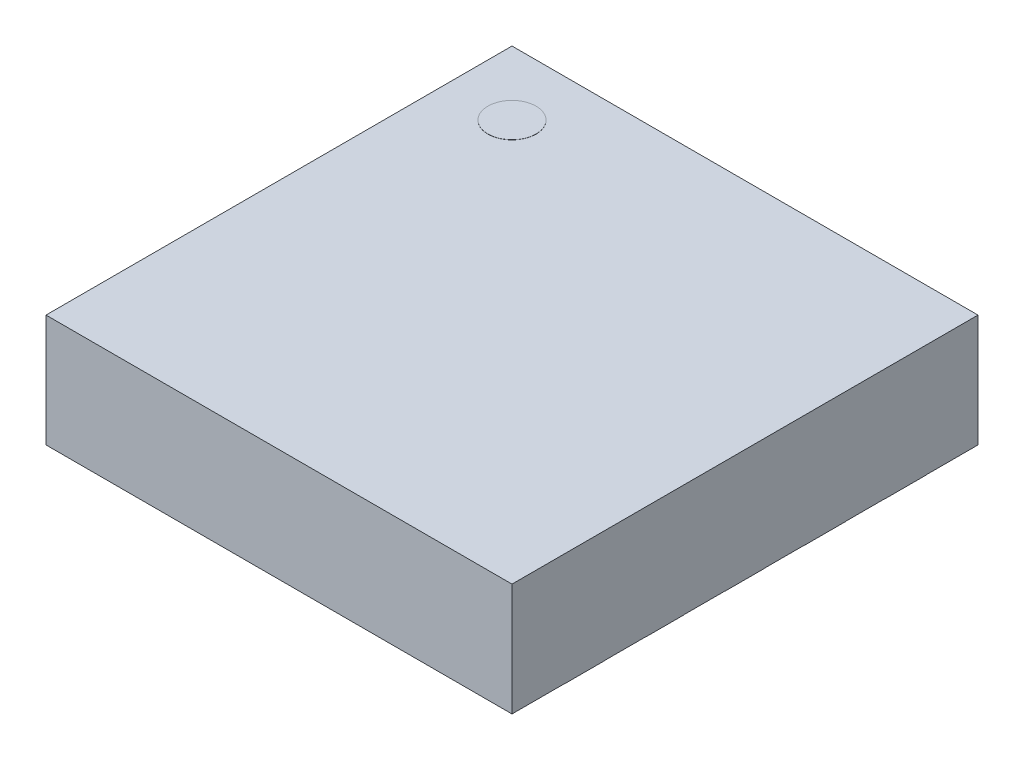
SolidWorks part; units mm, degrees
ref_plane "Front Plane" through (0, 0, 0) normal (0, 0, 1) x (1, 0, 0)
ref_plane "Top Plane" through (0, 0, 0) normal (0, 1, 0) x (1, 0, 0)
ref_plane "Right Plane" through (0, 0, 0) normal (1, 0, 0) x (0, 0, -1)
sketch "Sketch1" plane through (0, 0, 0) normal (0, 1, 0) x (1, 0, 0)
  line L1 (-1.45, 1.45) -> (1.45, 1.45)
  line L2 (-1.45, 1.45) -> (-1.45, -1.45)
  line L3 (-1.45, -1.45) -> (1.45, -1.45)
  line L4 (1.45, 1.45) -> (1.45, -1.45)
  line L5 (-1.45, 1.45) -> (1.45, -1.45) construction
  line L6 (-1.45, -1.45) -> (1.45, 1.45) construction
  point P0 (0, 0)
  dimension "D1" = 2.9
  dimension "D2" = 2.9
extrude "Boss-Extrude1" add sketch "Sketch1" along normal blind 0.7
sketch "Sketch2" plane through (0, 0, 0) normal (0, -1, 0) x (1, 0, 0)
  line L0 (0, 0) -> (-1.288, 0) construction
  line L1 (-1.45, -1.45) -> (-1.45, 1.45) construction
  line L2 (-1.45, 0.125) -> (-1.126, 0.125)
  line L3 (-1.45, 0.125) -> (-1.45, -0.125)
  line L4 (-1.45, -0.125) -> (-1.126, -0.125)
  line L5 (-1.126, 0.125) -> (-1.126, -0.125)
  line L6 (-1.45, 0.125) -> (-1.126, -0.125) construction
  line L7 (-1.45, -0.125) -> (-1.126, 0.125) construction
  line L8 (0, 0) -> (0, 0.6046) construction
  line L9 (-1.45, 0.625) -> (-1.45, 0.375)
  line L10 (-1.45, 0.625) -> (-1.126, 0.625)
  line L11 (-1.126, 0.625) -> (-1.126, 0.375)
  line L12 (-1.45, 0.375) -> (-1.126, 0.375)
  line L13 (-1.45, 1.125) -> (-1.45, 0.875)
  line L14 (-1.45, 1.125) -> (-1.126, 1.125)
  line L15 (-1.126, 1.125) -> (-1.126, 0.875)
  line L16 (-1.45, 0.875) -> (-1.126, 0.875)
  line L17 (-1.45, -1.125) -> (-1.126, -1.125)
  line L18 (-1.126, -1.125) -> (-1.126, -0.875)
  line L19 (-1.45, -0.875) -> (-1.126, -0.875)
  line L20 (-1.45, -1.125) -> (-1.45, -0.875)
  line L21 (-1.45, -0.625) -> (-1.126, -0.625)
  line L22 (-1.126, -0.625) -> (-1.126, -0.375)
  line L23 (-1.45, -0.375) -> (-1.126, -0.375)
  line L24 (-1.45, -0.625) -> (-1.45, -0.375)
  line L25 (1.45, -1.125) -> (1.45, -0.875)
  line L26 (1.45, -0.875) -> (1.126, -0.875)
  line L27 (1.126, -1.125) -> (1.126, -0.875)
  line L28 (1.45, -1.125) -> (1.126, -1.125)
  line L29 (1.45, -0.625) -> (1.45, -0.375)
  line L30 (1.45, -0.375) -> (1.126, -0.375)
  line L31 (1.126, -0.625) -> (1.126, -0.375)
  line L32 (1.45, -0.625) -> (1.126, -0.625)
  line L33 (1.45, -0.125) -> (1.126, -0.125)
  line L34 (1.126, 0.125) -> (1.126, -0.125)
  line L35 (1.45, 0.125) -> (1.126, 0.125)
  line L36 (1.45, 0.125) -> (1.45, -0.125)
  line L37 (1.45, 0.625) -> (1.126, 0.625)
  line L38 (1.126, 0.625) -> (1.126, 0.375)
  line L39 (1.45, 0.375) -> (1.126, 0.375)
  line L40 (1.45, 0.625) -> (1.45, 0.375)
  line L41 (1.45, 1.125) -> (1.126, 1.125)
  line L42 (1.126, 1.125) -> (1.126, 0.875)
  line L43 (1.45, 0.875) -> (1.126, 0.875)
  line L44 (1.45, 1.125) -> (1.45, 0.875)
  line L46 (-0.8, 1.15) -> (0.8, 1.15)
  line L47 (-0.8, 1.15) -> (-0.8, -1.15)
  line L48 (-0.8, -1.15) -> (0.8, -1.15)
  line L49 (0.8, 1.15) -> (0.8, -1.15)
  line L50 (-0.8, 1.15) -> (0.8, -1.15) construction
  line L51 (-0.8, -1.15) -> (0.8, 1.15) construction
  dimension "D1" = 0.324
  dimension "D2" = 0.25
  dimension "D3" = 3
  dimension "D4" = 1.6
  dimension "D5" = 2.3
extrude "Boss-Extrude2" add sketch "Sketch2" along normal blind 0.001
sketch "Sketch3" plane through (0, 0.7, 0) normal (0, 1, 0) x (1, 0, 0)
  line L0 (-1.45, 1.45) -> (-1.05, 1.05) construction
  line L1 (-1.45, 1.45) -> (-1.45, -1.45) construction
  circle A0 centre (-1.05, 1.05) radius 0.15
  dimension "D2" = 0.4
  dimension "D3" = 0.3
  dimension "D1" = 45
extrude "Boss-Extrude3" add sketch "Sketch3" along normal blind 0.001
